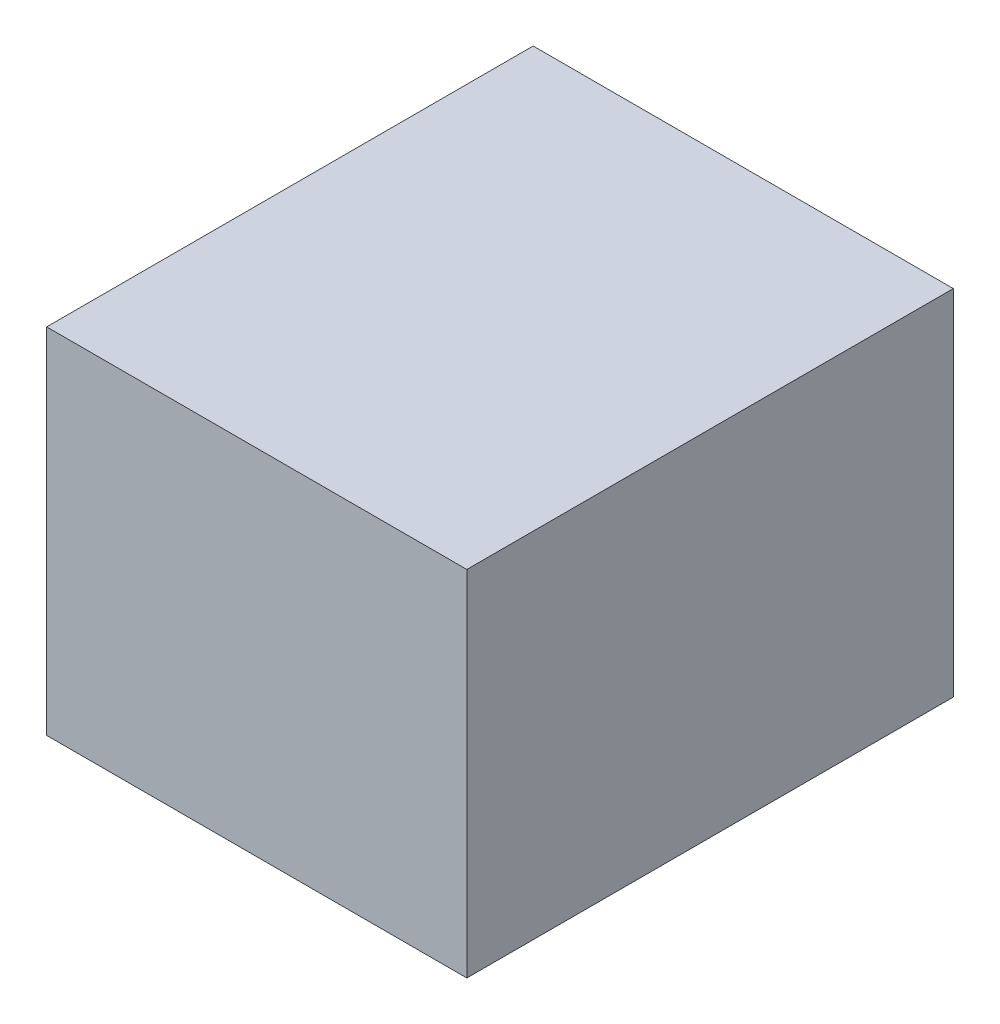
SolidWorks part; units mm, degrees
ref_plane "Front Plane" through (0, 0, 0) normal (0, 0, 1) x (1, 0, 0)
ref_plane "Top Plane" through (0, 0, 0) normal (0, 1, 0) x (1, 0, 0)
ref_plane "Right Plane" through (0, 0, 0) normal (1, 0, 0) x (0, 0, -1)
sketch "Sketch2" plane through (0, 0, 0) normal (0, 1, 0) x (1, 0, 0)
  line L1 (-19, -22) -> (19, -22)
  line L2 (-19, -22) -> (-19, 22)
  line L3 (-19, 22) -> (19, 22)
  line L4 (19, -22) -> (19, 22)
  line L5 (-19, -22) -> (19, 22) construction
  line L6 (-19, 22) -> (19, -22) construction
  point P0 (0, 0)
extrude "Boss-Extrude1" add sketch "Sketch2" along normal blind 32
